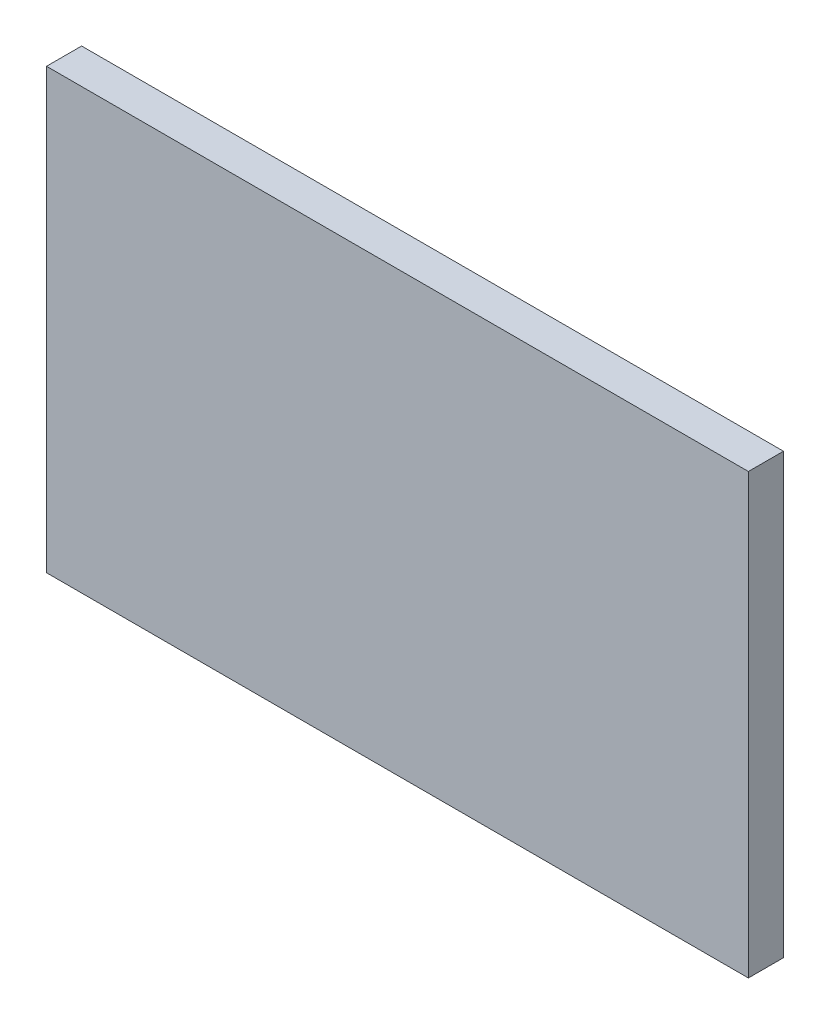
SolidWorks part; units mm, degrees
ref_plane "Front Plane" through (0, 0, 0) normal (0, 0, 1) x (1, 0, 0)
ref_plane "Top Plane" through (0, 0, 0) normal (0, 1, 0) x (1, 0, 0)
ref_plane "Right Plane" through (0, 0, 0) normal (1, 0, 0) x (0, 0, -1)
sketch "Sketch1" plane through (0, 0, 0) normal (0, 0, 1) x (1, 0, 0)
  line L1 (-500, -312.5) -> (500, -312.5)
  line L2 (-500, -312.5) -> (-500, 312.5)
  line L3 (-500, 312.5) -> (500, 312.5)
  line L4 (500, -312.5) -> (500, 312.5)
  line L5 (-500, -312.5) -> (500, 312.5) construction
  line L6 (-500, 312.5) -> (500, -312.5) construction
  point P0 (0, 0)
  dimension "D1" = 1000
  dimension "D2" = 625
extrude "Boss-Extrude1" add sketch "Sketch1" along normal blind 50
